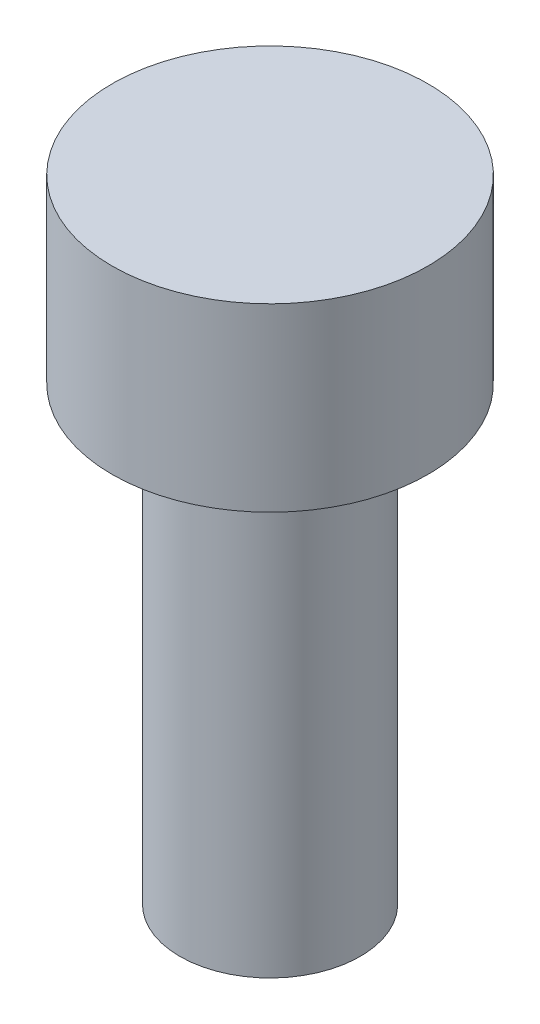
SolidWorks part; units mm, degrees
material "AISI 304"
ref_plane "Front" through (0, 0, 0) normal (0, 0, 1) x (1, 0, 0)
ref_plane "Top" through (0, 0, 0) normal (0, 1, 0) x (1, 0, 0)
ref_plane "Right" through (0, 0, 0) normal (1, 0, 0) x (0, 0, -1)
sketch "Sketch1" plane through (0, 0, 0) normal (0, 1, 0) x (1, 0, 0)
  circle A0 centre (0, 0) radius 2
  dimension "D1" = 4
extrude "Boss-Extrude1" add sketch "Sketch1" along normal blind 10
sketch "Sketch2" plane through (0, 10, 0) normal (0, 1, 0) x (1, 0, 0)
  circle A0 centre (0, 0) radius 3.5
  dimension "D1" = 7
extrude "Boss-Extrude2" add sketch "Sketch2" along normal blind 4
